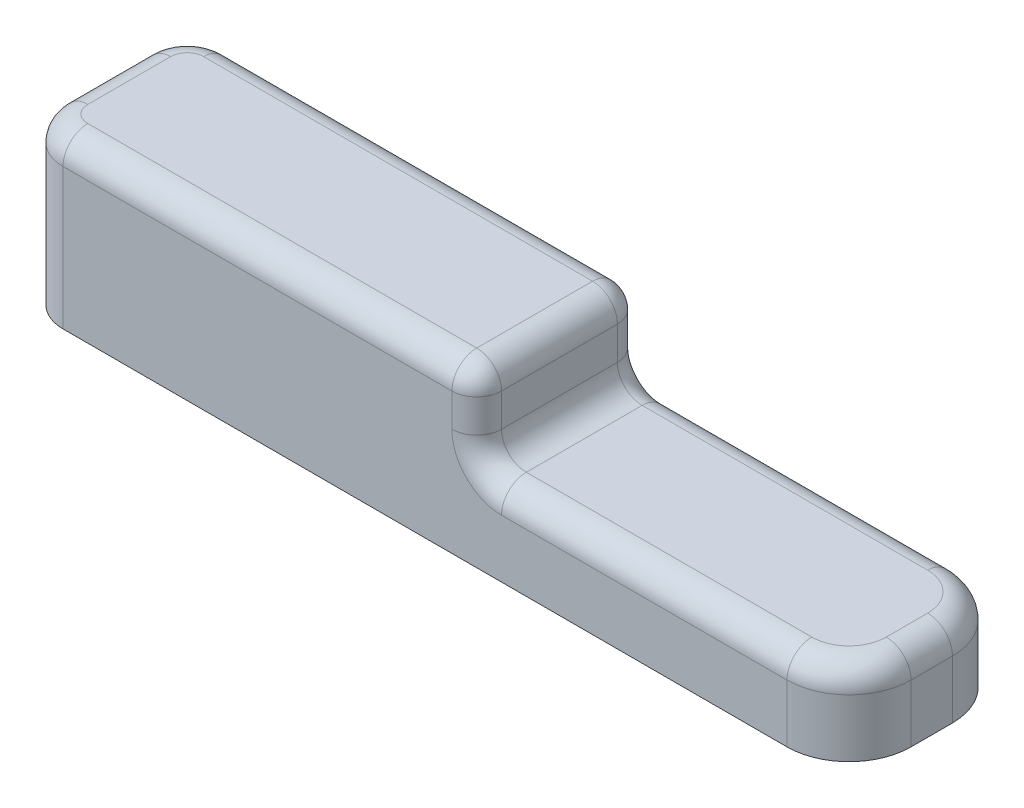
SolidWorks part; units mm, degrees
ref_plane "Front Plane" through (0, 0, 0) normal (0, 0, 1) x (1, 0, 0)
ref_plane "Top Plane" through (0, 0, 0) normal (0, 1, 0) x (1, 0, 0)
ref_plane "Right Plane" through (0, 0, 0) normal (1, 0, 0) x (0, 0, -1)
sketch "Sketch1" plane through (0, 0, 0) normal (0, 1, 0) x (1, 0, 0)
  line L1 (-50, 10) -> (50, 10)
  line L2 (-50, 10) -> (-50, -10)
  line L3 (-50, -10) -> (50, -10)
  line L4 (50, 10) -> (50, -10)
  line L5 (-50, 10) -> (50, -10) construction
  line L6 (-50, -10) -> (50, 10) construction
  point P0 (0, 0)
  dimension "D1" = 20
  dimension "D2" = 100
extrude "Boss-Extrude1" add sketch "Sketch1" along normal blind 20
fillet "Fillet1" radius 5 2 edges at (-50, 10, -10) (-50, 10, 10)
fillet "Fillet2" radius 7.5 2 edges at (50, 10, -10) (50, 10, 10)
sketch "Sketch3" plane through (0, 0, 10) normal (0, 0, 1) x (1, 0, 0)
  line L0 (-45, 20) -> (42.5, 20) construction
  line L5 (5, 20) -> (50, 20)
  line L6 (5, 20) -> (5, 10)
  line L7 (5, 10) -> (50, 10)
  line L8 (50, 20) -> (50, 10)
  line L9 (50, 20) -> (50, 0) construction
  line L10 (-45, 0) -> (42.5, 0) construction
  point P6 (50, 6.5295)
  dimension "D1" = 45
  dimension "D2" = 10
extrude "Cut-Extrude1" cut sketch "Sketch3" against normal through all both and the other way through all
fillet "Fillet3" radius 3 14 edges at (5, 15, -10) (5, 15, 10) (5, 10, 0) (23.75, 10, -10) (47.8033, 10, -7.8033) (50, 10, 0) (47.8033, 10, 7.8033) (23.75, 10, 10) (-48.5355, 20, -8.5355) (-50, 20, 0) (-48.5355, 20, 8.5355) (-20, 20, 10) (-20, 20, -10) (5, 20, 0)
shell "Shell1" thickness 1
sketch "Sketch4" plane through (0, 0, 0) normal (0, -1, 0) x (1, 0, 0)
  line L0 (2.5, 7.5) -> (42.5, 7.5) construction
  line L1 (42.5, 7.5) -> (42.5, -7.5) construction
  line L2 (42.5, -7.5) -> (2.5, -7.5) construction
  line L3 (2.5, -7.5) -> (2.5, 7.5) construction
  line L4 (2.5, 0) -> (42.5, 0) construction
  line L5 (-45, 9) -> (42.5, 9) construction
  line L6 (50, 2.5) -> (50, -2.5) construction
  line L7 (1.5, -7.5) -> (1.5, -9)
  line L8 (-45, -9) -> (2, -9) construction
  line L9 (3.5, -7.5) -> (3.5, -9)
  line L10 (42.5, -9) -> (-45, -9) construction
  line L11 (3.5, -9) -> (1.5, -9)
  line L12 (1.5, 7.5) -> (1.5, 9)
  line L13 (2, 9) -> (-45, 9) construction
  line L14 (1.5, 9) -> (3.5, 9)
  line L15 (3.5, 7.5) -> (3.5, 9)
  line L16 (41.5, -7.5) -> (41.5, -9)
  line L17 (41.5, -9) -> (43.5, -9)
  line L18 (43.5, -9) -> (43.5, -7.5)
  line L19 (41.5, 7.5) -> (41.5, 9)
  line L20 (42.5, 9) -> (8, 9) construction
  line L21 (41.5, 9) -> (43.5, 9)
  line L22 (43.5, 9) -> (43.5, 7.5)
  line L23 (47, 2.4312) -> (49, 2.4312)
  line L24 (49, 2.4312) -> (49, -1.5688)
  line L25 (49, -1.5688) -> (47, -1.5688)
  line L26 (47, 2.5) -> (47, -2.5) construction
  line L27 (49, -2.5) -> (49, 2.5) construction
  line L31 (-49, 5) -> (-49, -5) construction
  line L32 (-47, 2) -> (-49, 2)
  line L33 (-49, 2) -> (-49, -2)
  line L34 (-49, -5) -> (-49, 5) construction
  line L35 (-49, -2) -> (-47, -2)
  arc A0 (1.5, 7.5) -> (3.5, 7.5) centre (2.5, 7.5) ccw
  arc A1 (3.5, -7.5) -> (1.5, -7.5) centre (2.5, -7.5) ccw
  arc A2 (41.5, 7.5) -> (43.5, 7.5) centre (42.5, 7.5) ccw
  arc A3 (43.5, -7.5) -> (41.5, -7.5) centre (42.5, -7.5) ccw
  arc A4 (47, 2.4312) -> (47, -1.5688) centre (47, 0.4312) ccw
  arc A6 (-47, -2) -> (-47, 2) centre (-47, 0) ccw
  dimension "D1" = 15
  dimension "D4" = 2
  dimension "D7" = 2
  dimension "D10" = 2
  dimension "D2" = 40
  dimension "D3" = 9
  dimension "D5" = 15
  dimension "D6" = 7.5
  dimension "D8" = 2
  dimension "D9" = 1
extrude "Boss-Extrude3" add sketch "Sketch4" against normal up to body separate body
sketch "Sketch9" plane through (0, 0, 0) normal (0, -1, 0) x (1, 0, 0)
  point P0 (-47, 0)
  point P1 (47, 0.4312)
  point P3 (2.5, 7.5)
  point P5 (2.5, -7.5)
  point P7 (42.5, -7.5)
  point P9 (42.5, 7.5)
hole_wizard "M1.2x0.25 Tapped Hole2" positions "Sketch10" profile "Sketch11" tap size "M1.2x0.25" standard "ISO"
sketch "Sketch10" plane through (0, 0, 0) normal (0, -1, 0) x (-1, 0, 0)
  point P0 (-2.5, -7.5)
  point P3 (-2.5, 7.5)
  point P6 (-42.5, 7.5)
  point P9 (-42.5, -7.5)
sketch "Sketch11" plane through (2.5, 0, 7.5) normal (1, 0, 0) x (0, 0, -1)
  line L0 (0, 0) -> (0, 3.9354)
  line L1 (0, 3.9354) -> (0.475, 3.65)
  line L2 (0.475, 3.65) -> (0.475, 0)
  line L5 (0.475, 0) -> (0, 0)
  line L10 (0, 3.9354) -> (-0.475, 3.65) construction
  line L11 (0, -6.35) -> (0, 107.95) construction
  dimension "Tap Drill Dia." = 0.95
  dimension "Tap Drill Depth" = 3.65
  dimension "Drill Angle" = 118
cosmetic thread "Hole Thread5" parameters "D1"=2.4, "D2"=1.2
cosmetic thread "Hole Thread6" parameters "D1"=2.4, "D2"=1.2
cosmetic thread "Hole Thread7" parameters "D1"=2.4, "D2"=1.2
cosmetic thread "Hole Thread8" parameters "D1"=2.4, "D2"=1.2
hole_wizard "M3 Tapped Hole1" positions "Sketch12" profile "Sketch13" tap size "M3" standard "ISO"
sketch "Sketch12" plane through (0, 0, 0) normal (0, -1, 0) x (-1, 0, 0)
  point P0 (-47, -0.4312)
  point P3 (47, 0)
sketch "Sketch13" plane through (47, 0, 0.4312) normal (1, 0, 0) x (0, 0, -1)
  line L0 (0, 0) -> (0, 9.2511)
  line L1 (0, 9.2511) -> (1.25, 8.5)
  line L2 (1.25, 8.5) -> (1.25, 0)
  line L5 (1.25, 0) -> (0, 0)
  line L10 (0, 9.2511) -> (-1.25, 8.5) construction
  line L11 (0, -6.35) -> (0, 107.95) construction
  dimension "Tap Drill Dia." = 2.5
  dimension "Tap Drill Depth" = 8.5
  dimension "Drill Angle" = 118
cosmetic thread "Hole Thread9" parameters "D1"=6, "D2"=3
cosmetic thread "Hole Thread10" parameters "D1"=6, "D2"=3
